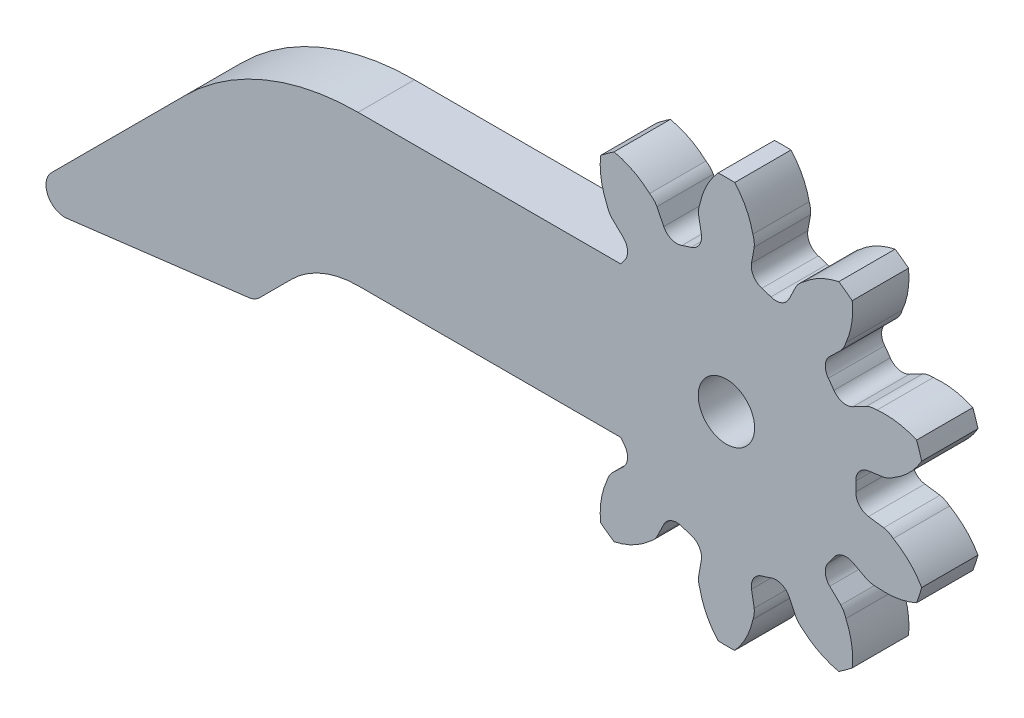
SolidWorks part; units mm, degrees
material "Acrílico (médio-alto impacto)"
ref_plane "Plano frontal" through (0, 0, 0) normal (0, 0, 1) x (1, 0, 0)
ref_plane "Plano superior" through (0, 0, 0) normal (0, 1, 0) x (1, 0, 0)
ref_plane "Plano direito" through (0, 0, 0) normal (1, 0, 0) x (0, 0, -1)
sketch "Posicionamentos" plane through (0, 0, 0) normal (0, 0, 1) x (1, 0, 0)
  circle A0 centre (0, 0) radius 10.8
  circle A1 centre (0, 0) radius 9
  circle A2 centre (0, 0) radius 6.8994
  circle A3 centre (0, 0) radius 8.4572
  dimension "De" = 21.6
  dimension "DP" = 18
  dimension "DI" = 13.7988
  dimension "DB" = 16.9145
sketch "Dente" plane through (0, 0, 0) normal (0, 0, 1) x (1, 0, 0)
  line L0 (0, 0) -> (0, 10.8) construction
  line L1 (0, 0) -> (0, 10.8) construction
  line L2 (1.4803, 8.3267) -> (1.2076, 6.7929)
  line L3 (1.4079, 8.8892) -> (0, 0) construction
  line L4 (-1.4803, 8.3267) -> (-1.2076, 6.7929)
  circle A0 centre (0, 0) radius 10.8 construction
  arc A1 (0.4416, 10.791) -> (1.4079, 8.8892) centre (-2.6083, 8.045) cw
  circle A2 centre (0, 0) radius 9 construction
  arc A3 (1.4079, 8.8892) -> (1.4803, 8.3267) centre (0.2448, 8.4537) cw
  circle A4 centre (0, 0) radius 8.4572 construction
  circle A5 centre (0, 0) radius 6.8994 construction
  arc A6 (-1.4079, 8.8892) -> (-1.4803, 8.3267) centre (-0.2448, 8.4537) ccw
  arc A7 (-0.4416, 10.791) -> (-1.4079, 8.8892) centre (2.6083, 8.045) ccw
  arc A8 (-1.2076, 6.7929) -> (1.2076, 6.7929) centre (0, 0) cw
  arc A9 (-0.4416, 10.791) -> (0.4416, 10.791) centre (0, 0) cw
  arc A10 (-1.4079, 8.8892) -> (1.4079, 8.8892) centre (0, 0) cw construction
  dimension "R" = 4.104
  dimension "R1" = 1.242
  dimension "alpha" = 9
  dimension "Aposicionador" = 0
  dimension "D1" = 2.8274
sketch "Braço" plane through (0, 0, 0) normal (0, 0, 1) x (1, 0, 0)
  line L0 (0, 0) -> (-25, 0) construction
  line L1 (0, 4) -> (-25, 4)
  line L2 (-25, 4) -> (-38, -9)
  line L3 (-38, -9) -> (-25.1027, -7.4164)
  line L4 (-25.1027, -7.4164) -> (-21.6863, -4)
  line L5 (-21.6863, -4) -> (0, -4)
  line L6 (0, -4) -> (0, 4)
  line L7 (-38, -9) -> (-22.7813, -9) construction
  line L8 (-29.0514, -0.0514) -> (-23.3945, -5.7082) construction
  circle A1 centre (0, 0) radius 9 construction
  dimension "D1" = 38
  dimension "D2" = 7
  dimension "D3" = 135
  dimension "D4" = 8
extrude "Base" add sketch "Posicionamentos" along normal blind 3 contours A2
extrude "Base Dente" add sketch "Dente" along normal through all
fillet "Raio Dente" radius 0.7789 2 edges at (-1.2076, 6.7929, 1.5) (1.2076, 6.7929, 1.5)
pattern_circular "PadrãoCircular1" count 10 over 360 about axis through (0, 0, 0) along (0, 0, 1) skipping 7, 8 of "Base Dente", "Raio Dente"
extrude "Ressalto-extrusão3" add sketch "Braço" along normal through all contours L5 L6 L1 L2 L3 L4
hole_wizard "Furo de diâmetro Ø3.0 (3)1" positions "Esboço4" profile "Esboço5" hole size "Ø3.0" standard "ISO" end condition through all
sketch "Esboço4" plane through (0, 0, 3) normal (0, 0, 1) x (1, 0, 0)
  point P0 (0, 0)
sketch "Esboço5" plane through (0, 0, 3) normal (1, 0, 0) x (0, -1, 0)
  line L0 (0, 0) -> (0, 3)
  line L1 (0, 3) -> (1.5, 3)
  line L2 (1.5, 3) -> (1.5, 0)
  line L5 (1.5, 0) -> (0, 0)
  line L11 (0, -6.35) -> (0, 107.95) construction
  dimension "Thru Hole Dia." = 3
  dimension "Thru Hole Depth" = 3
fillet "Filete2" radius 5 1 edges at (-21.6863, -4, 1.5)
fillet "Filete3" radius 13 1 edges at (-25, 4, 1.5)
fillet "Filete4" radius 1 2 edges at (-38, -9, 1.5) (-25.1027, -7.4164, 1.5)
equation "\"Z\"= \"Z@Padrão\""
equation "\"M\"= \"DP\" / \"Z\"'Módulo"
equation "\"DP\"= \"DP@Padrão\""
equation "\"P\"= \"M\" * pi'Passo"
equation "\"S\"= \"P\" / 2'Espessura Circular"
equation "\"V\"= \"S\"'Vão"
equation "\"sc\"= 1"
equation "\"de\"= \"M\" * ( \"Z\" + 2 )'Diâmetro Externo"
equation "\"di\"= \"M\" * ( \"Z\" - 2.334 )'Diâmetro Interno"
equation "\"Phi\"= 20'ângulo de pressão"
equation "\"db\"= \"DP\" * cos ( \"Phi\" )'Diâmetro do círculo de base"
equation "\"a\"= \"M\"'Altura da cabeça do dente"
equation "\"b\"= 1.167 * \"M\"'Altura do pé do dente"
equation "\"h\"= \"a\" + \"b\"'Altura do dente"
equation "\"e\"= .167 * \"M\"'Folga no pé do dente"
equation "\"alpha\"= 90 / \"Z\"'ângulo do dente"
equation "\"f\"= \"ValorF@Padrão\""
equation "\"f1\"= \"ValorF1@Padrão\""
equation "\"r\"= \"f\" * \"M\" 'Raio do dente"
equation "\"r1\"= \"f1\" * \"M\"'Rario 1 do dente"
equation "\"De@Posicionamentos\" = \"de\""
equation "\"DP@Posicionamentos\" = \"DP\""
equation "\"DI@Posicionamentos\" = \"di\""
equation "\"DB@Posicionamentos\" = \"db\""
equation "\"R@Dente\" = \"r\""
equation "\"R1@Dente\" = \"r1\""
equation "\"alpha@Dente\" = \"alpha\""
equation "\"D1@PadrãoCircular1\"=\"Z\""
equation "\"rd\"= ( \"db\" - \"di\" ) / 4"
equation "\"D1@Raio Dente\"=\"rd\""
equation "\"D1@Dente\"=\"S\""
